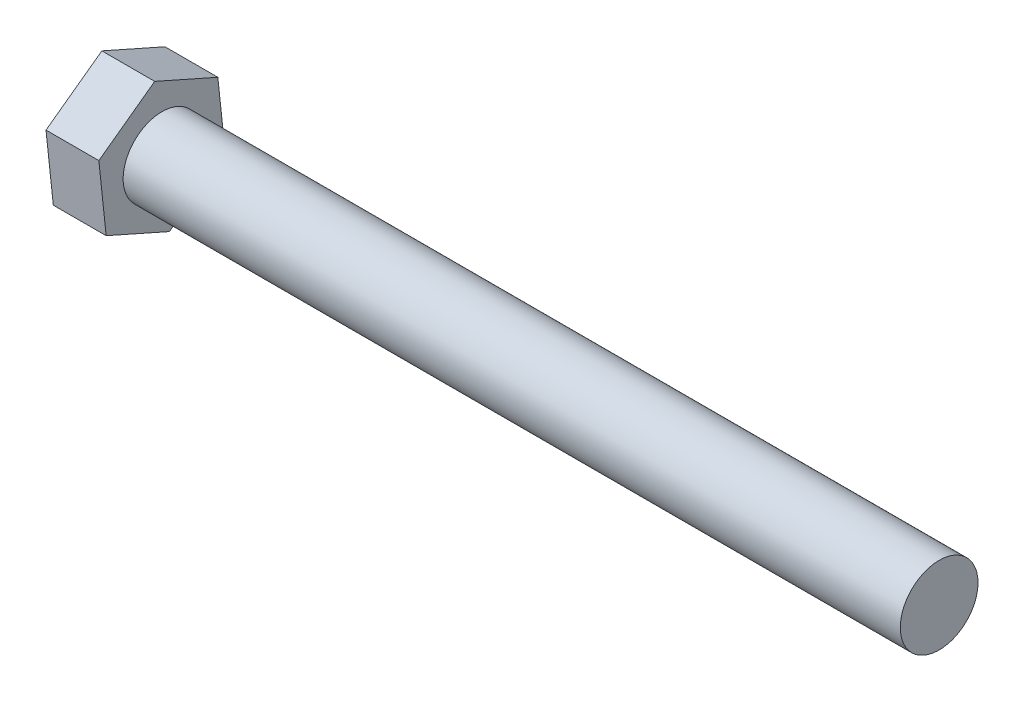
SolidWorks part; units mm, degrees
ref_plane "Front Plane" through (0, 0, 0) normal (0, 0, 1) x (1, 0, 0)
ref_plane "Top Plane" through (0, 0, 0) normal (0, 1, 0) x (1, 0, 0)
ref_plane "Right Plane" through (0, 0, 0) normal (1, 0, 0) x (0, 0, -1)
sketch "Sketch1" plane through (0, 0, 0) normal (1, 0, 0) x (0, 0, -1)
  line L1 (3.5935, 2.6172) -> (-0.4698, 4.4207)
  line L2 (-0.4698, 4.4207) -> (-4.0633, 1.8035)
  line L3 (-4.0633, 1.8035) -> (-3.5935, -2.6172)
  line L4 (-3.5935, -2.6172) -> (0.4698, -4.4207)
  line L5 (0.4698, -4.4207) -> (4.0633, -1.8035)
  line L6 (4.0633, -1.8035) -> (3.5935, 2.6172)
  circle A0 centre (0, 0) radius 3.85 construction
  dimension "D1" = 7.7
extrude "Boss-Extrude1" add sketch "Sketch1" along normal blind 3.4
sketch "Sketch2" plane through (3.4, 0, 0) normal (1, 0, 0) x (0, 0, -1)
  circle A0 centre (0, 0) radius 2.5
  dimension "D1" = 5
extrude "Boss-Extrude2" add sketch "Sketch2" along normal blind 50
